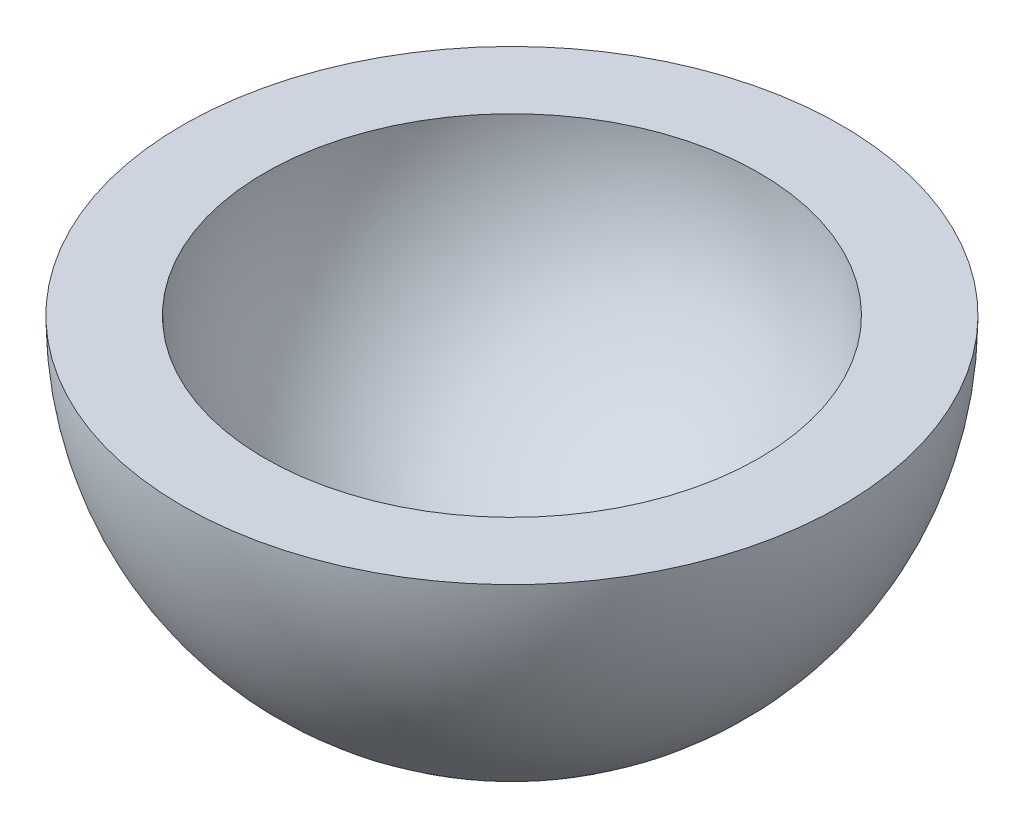
SolidWorks part; units mm, degrees
ref_plane "Front Plane" through (0, 0, 0) normal (0, 0, 1) x (1, 0, 0)
ref_plane "Top Plane" through (0, 0, 0) normal (0, 1, 0) x (1, 0, 0)
ref_plane "Right Plane" through (0, 0, 0) normal (1, 0, 0) x (0, 0, -1)
sketch "Sketch1" plane through (0, 0, 0) normal (0, 1, 0) x (1, 0, 0)
  line L0 (0, 8) -> (0, -8)
  arc A0 (0, 8) -> (0, -8) centre (0, 0) ccw
  dimension "D1" = 16
revolve "Revolve1" add sketch "Sketch1" angle 180 about L0
sketch "Sketch2" plane through (0, 0, 0) normal (0, 1, 0) x (1, 0, 0)
  line L0 (0, 6) -> (0, -6)
  arc A0 (0, 6) -> (0, -6) centre (0, 0) ccw
  dimension "D1" = 12
revolve "Cut-Revolve1" cut sketch "Sketch2" angle 360 about L0
